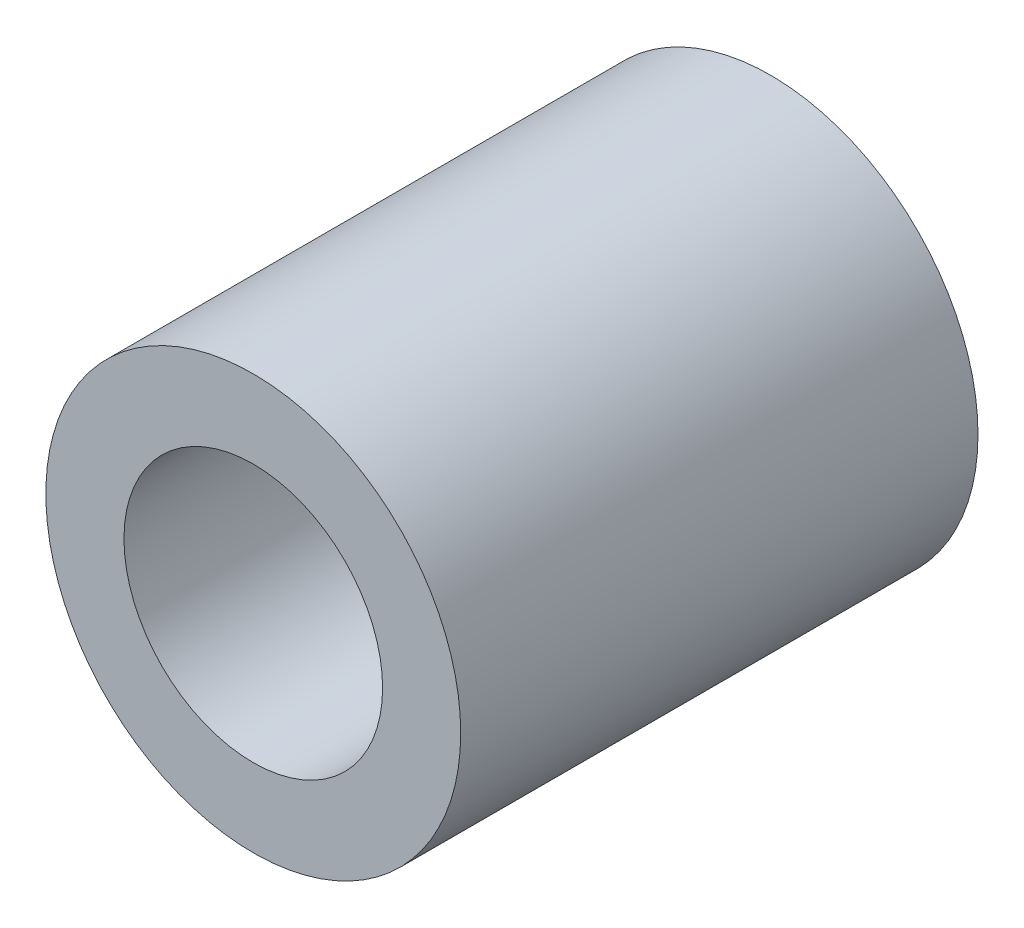
SolidWorks part; units mm, degrees
ref_plane "Front Plane" through (0, 0, 0) normal (0, 0, 1) x (1, 0, 0)
ref_plane "Top Plane" through (0, 0, 0) normal (0, 1, 0) x (1, 0, 0)
ref_plane "Right Plane" through (0, 0, 0) normal (1, 0, 0) x (0, 0, -1)
sketch "Sketch1" plane through (0, 0, 0) normal (0, 0, 1) x (1, 0, 0)
  circle A0 centre (0, 0) radius 4.01
  circle A1 centre (0, 0) radius 2.5
  dimension "D1" = 8.02
  dimension "ID" = 5
extrude "Extrude1" add sketch "Sketch1" along normal mid plane 10
sketch "Sketch2" plane through (0, 0, 0) normal (1, 0, 0) x (0, 0, -1)
  line L0 (-5, -2.5) -> (5, -2.5) construction
  line L3 (5, 2.5) -> (-5, 2.5) construction
  line L5 (-5, -2.5) -> (5, -2.5)
  line L6 (5, 2.5) -> (-5, 2.5)
sketch "Sketch4" plane through (0, 0, 5) normal (0, 0, 1) x (1, 0, 0)
  line L0 (0, 0) -> (-1.7678, 1.7678)
  line L1 (0, -5.5) -> (0, 5.5) construction
  circle A0 centre (0, 0) radius 2.5 construction
  dimension "D1" = 45
